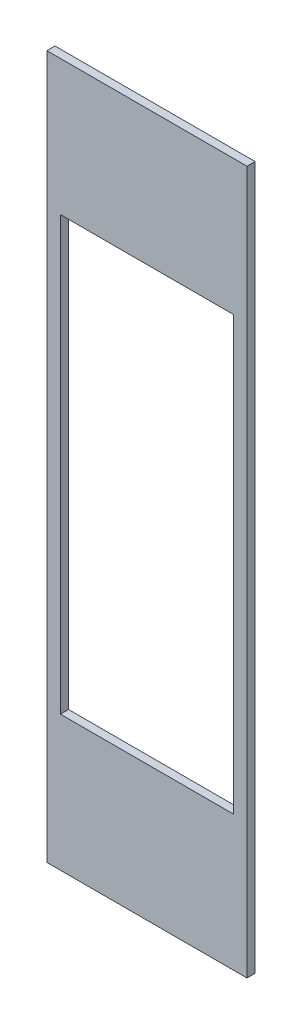
SolidWorks part; units mm, degrees
ref_plane "Plano frontal" through (0, 0, 0) normal (0, 0, 1) x (1, 0, 0)
ref_plane "Plano superior" through (0, 0, 0) normal (0, 1, 0) x (1, 0, 0)
ref_plane "Plano direito" through (0, 0, 0) normal (1, 0, 0) x (0, 0, -1)
sketch "Esboço1" plane through (0, 0, 0) normal (0, 0, 1) x (1, 0, 0)
  line L1 (-185, 650) -> (185, 650)
  line L2 (-185, 650) -> (-185, -650)
  line L3 (-185, -650) -> (185, -650)
  line L4 (185, 650) -> (185, -650)
  line L5 (-185, 650) -> (185, -650) construction
  line L6 (-185, -650) -> (185, 650) construction
  point P0 (0, 0)
  dimension "D1" = 370
  dimension "D2" = 1300
extrude "Ressalto-extrusão1" add sketch "Esboço1" along normal blind 15
sketch "Esboço2" plane through (0, 0, 15) normal (0, 0, 1) x (1, 0, 0)
  line L1 (-160, 400) -> (160, 400)
  line L2 (-160, 400) -> (-160, -400)
  line L3 (-160, -400) -> (160, -400)
  line L4 (160, 400) -> (160, -400)
  line L5 (-160, 400) -> (160, -400) construction
  line L6 (-160, -400) -> (160, 400) construction
  point P0 (0, 0)
  dimension "D1" = 320
  dimension "D2" = 800
  dimension "D3" = 400
extrude "Corte-extrusão1" cut sketch "Esboço2" against normal blind 15
